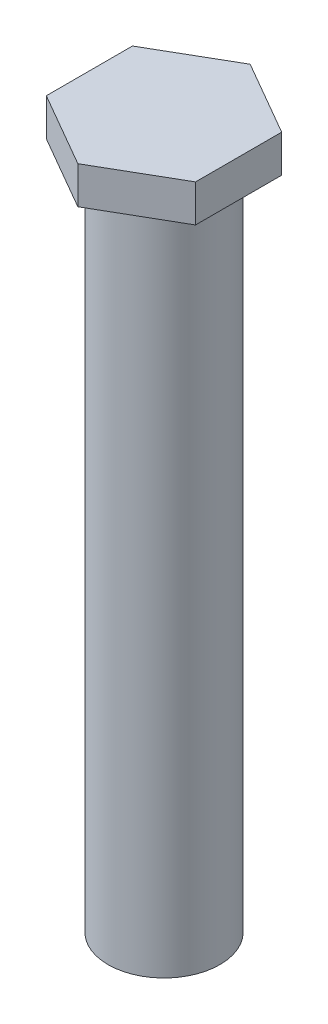
SolidWorks part; units mm, degrees
material "Cast Alloy Steel"
ref_plane "Front Plane" through (0, 0, 0) normal (0, 0, 1) x (1, 0, 0)
ref_plane "Top Plane" through (0, 0, 0) normal (0, 1, 0) x (1, 0, 0)
ref_plane "Right Plane" through (0, 0, 0) normal (1, 0, 0) x (0, 0, -1)
sketch "Sketch1" plane through (0, 0, 0) normal (0, 1, 0) x (1, 0, 0)
  circle A0 centre (0, 0) radius 9.525
  dimension "D1" = 19.05
extrude "Boss-Extrude1" add sketch "Sketch1" along normal blind 114.3
sketch "Sketch2" plane through (0, 114.3, 0) normal (0, 1, 0) x (1, 0, 0)
  line L1 (12.7, 7.3323) -> (0, 14.6647)
  line L2 (0, 14.6647) -> (-12.7, 7.3323)
  line L3 (-12.7, 7.3323) -> (-12.7, -7.3323)
  line L4 (-12.7, -7.3323) -> (0, -14.6647)
  line L5 (0, -14.6647) -> (12.7, -7.3323)
  line L6 (12.7, -7.3323) -> (12.7, 7.3323)
  circle A0 centre (0, 0) radius 12.7 construction
  dimension "D1" = 25.4
extrude "Boss-Extrude2" add sketch "Sketch2" along normal blind 6.35
